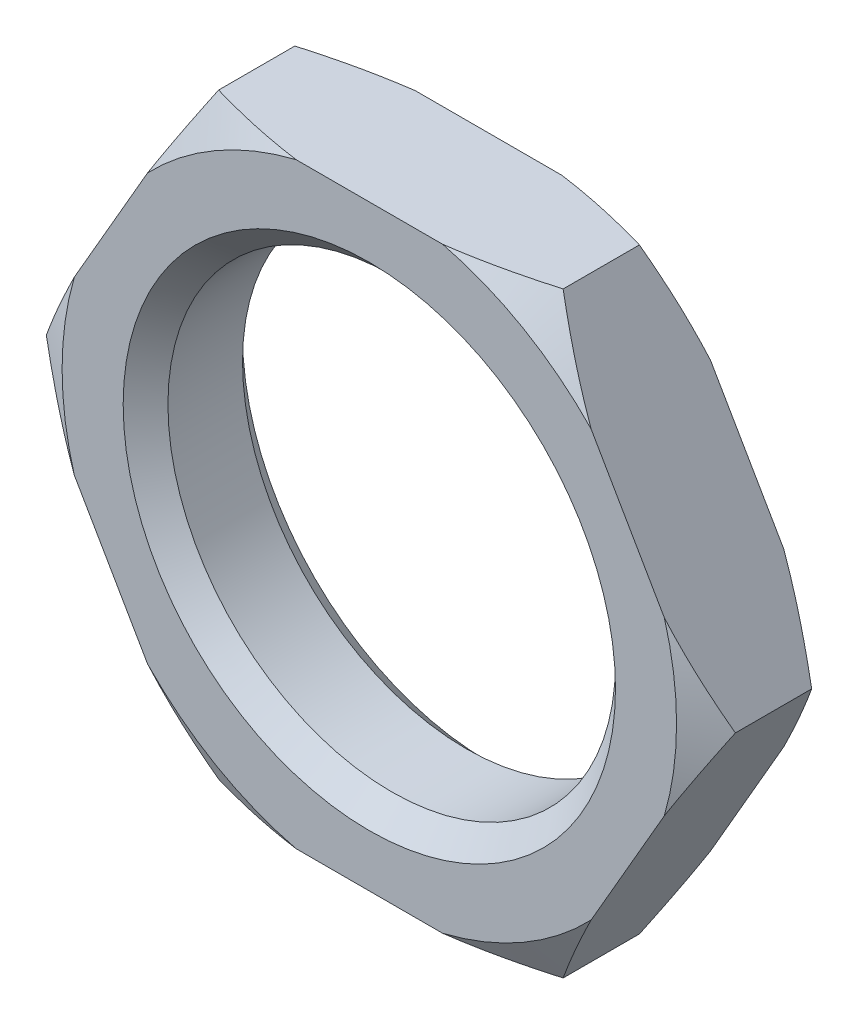
SolidWorks part; units mm, degrees
material "Laiton"
ref_plane "Plan de face" through (0, 0, 0) normal (0, 0, 1) x (1, 0, 0)
ref_plane "Plan de dessus" through (0, 0, 0) normal (0, 1, 0) x (1, 0, 0)
ref_plane "Plan de droite" through (0, 0, 0) normal (1, 0, 0) x (0, 0, -1)
sketch "Esquisse1" plane through (0, 0, 0) normal (0, 0, 1) x (1, 0, 0)
  line L1 (4.6188, 0) -> (2.3094, 4)
  line L2 (2.3094, 4) -> (-2.3094, 4)
  line L3 (-2.3094, 4) -> (-4.6188, 0)
  line L4 (-4.6188, 0) -> (-2.3094, -4)
  line L5 (-2.3094, -4) -> (2.3094, -4)
  line L6 (2.3094, -4) -> (4.6188, 0)
  circle A0 centre (0, 0) radius 4 construction
  circle A1 centre (0, 0) radius 3
  dimension "D2" = 6
  dimension "D1" = 8
extrude "Boss.-Extru.1" add sketch "Esquisse1" along normal blind 1.6
sketch "Esquisse2" plane through (0, 0, 0) normal (0, 1, 0) x (1, 0, 0)
  line L0 (-4.1188, 0) -> (-4.6188, -0.2887)
  line L1 (-4.6188, -0.2887) -> (-4.6188, -1.3113)
  line L2 (-4.6188, -1.3113) -> (-4.1188, -1.6)
  line L3 (-4.1188, -1.6) -> (-5.6188, -1.6)
  line L4 (-5.6188, -1.6) -> (-5.6188, 0)
  line L5 (-5.6188, 0) -> (-4.1188, 0)
  line L6 (-4.6188, -1.6) -> (-4.6188, 0) construction
  line L8 (-2.3094, 0) -> (-4.6188, 0) construction
  line L9 (-2.3094, -1.6) -> (-4.6188, -1.6) construction
  line L10 (-4.1188, 0) -> (-4.1188, -1.6) construction
  line L11 (0, 0) -> (0, -1.6) construction
  line L12 (2.3094, -1.6) -> (-2.3094, -1.6) construction
  dimension "D1" = 30
  dimension "D2" = 30
  dimension "D3" = 1
  dimension "D4" = 0.5
revolve "Enlèvement de matière-Révolution1" cut sketch "Esquisse2" angle 360 about L11
chamfer "Chanfrein1" distance 0.3 angle 45 2 edges at (3, 0, 1.6) (3, 0, 0)
